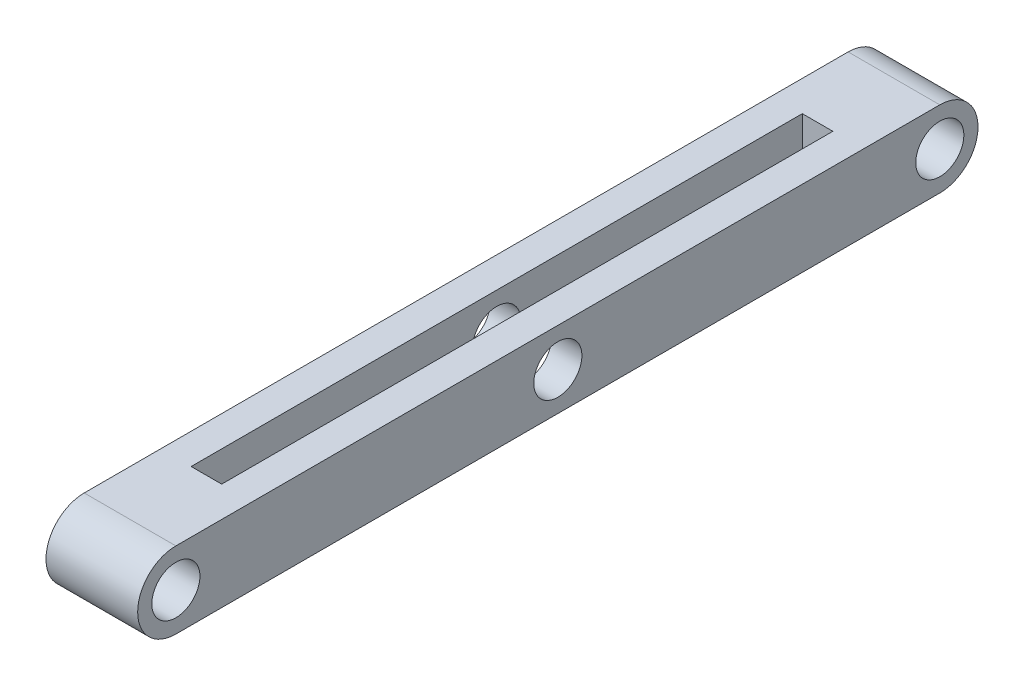
SolidWorks part; units mm, degrees
ref_plane "Front Plane" through (0, 0, 0) normal (0, 0, 1) x (1, 0, 0)
ref_plane "Top Plane" through (0, 0, 0) normal (0, 1, 0) x (1, 0, 0)
ref_plane "Right Plane" through (0, 0, 0) normal (1, 0, 0) x (0, 0, -1)
sketch "Sketch1" plane through (0, 0, 0) normal (1, 0, 0) x (0, 0, -1)
  line L0 (-77.47, 8.4137) -> (49.53, 8.4137)
  line L2 (49.53, -4.2862) -> (-77.47, -4.2863)
  arc A0 (-77.47, -4.2863) -> (-77.47, 8.4137) centre (-77.47, 2.0637) cw
  arc A1 (49.53, -4.2862) -> (49.53, 8.4137) centre (49.53, 2.0637) ccw
  dimension "D1" = 12.7
  dimension "D2" = 127
extrude "Boss-Extrude1" add sketch "Sketch1" along normal blind 15.24
hole_wizard "Ø8.0mm Dowel Hole1" positions "Sketch4" profile "Sketch3" hole size "Ø8.0" standard "ANSI Metric" end condition through all
sketch "Sketch4" plane through (15.24, 0, 0) normal (1, 0, 0) x (0, 0, -1)
  line L1 (-13.97, 8.4137) -> (-13.97, -4.2863) construction
  line L2 (49.53, 8.4137) -> (-77.47, 8.4137) construction
  line L3 (-77.47, -4.2863) -> (49.53, -4.2862) construction
  arc A0 (-77.47, 8.4137) -> (-77.47, -4.2863) centre (-77.47, 2.0637) ccw construction
  arc A1 (49.53, -4.2862) -> (49.53, 8.4137) centre (49.53, 2.0637) ccw construction
  point P0 (-77.47, 2.0637)
  point P2 (49.53, 2.0637)
  point P12 (-13.97, 2.0637)
  point P22 (0, 0)
sketch "Sketch3" plane through (15.24, 2.0637, 77.47) normal (0, 1, 0) x (0, 0, -1)
  line L0 (0, 0) -> (0, 15.24)
  line L1 (0, 15.24) -> (4, 15.24)
  line L2 (4, 15.24) -> (4, 0)
  line L5 (4, 0) -> (0, 0)
  line L11 (0, -6.35) -> (0, 107.95) construction
  dimension "Thru Hole Dia." = 8
  dimension "Thru Hole Depth" = 15.24
sketch "Sketch5" plane through (0, 8.4137, 0) normal (0, 1, 0) x (1, 0, 0)
  line L0 (15.24, -13.97) -> (0, -13.97) construction
  line L1 (5.08, -64.77) -> (10.16, -64.77)
  line L2 (5.08, -64.77) -> (5.08, 36.83)
  line L3 (5.08, 36.83) -> (10.16, 36.83)
  line L4 (10.16, -64.77) -> (10.16, 36.83)
  line L5 (15.24, 49.53) -> (15.24, -77.47) construction
  line L6 (0, 49.53) -> (0, -77.47) construction
  line L7 (7.62, -64.77) -> (7.62, 36.83) construction
  point P10 (10.16, -13.97)
  dimension "D1" = 5.08
  dimension "D2" = 101.6
extrude "Cut-Extrude1" cut sketch "Sketch5" against normal through all
